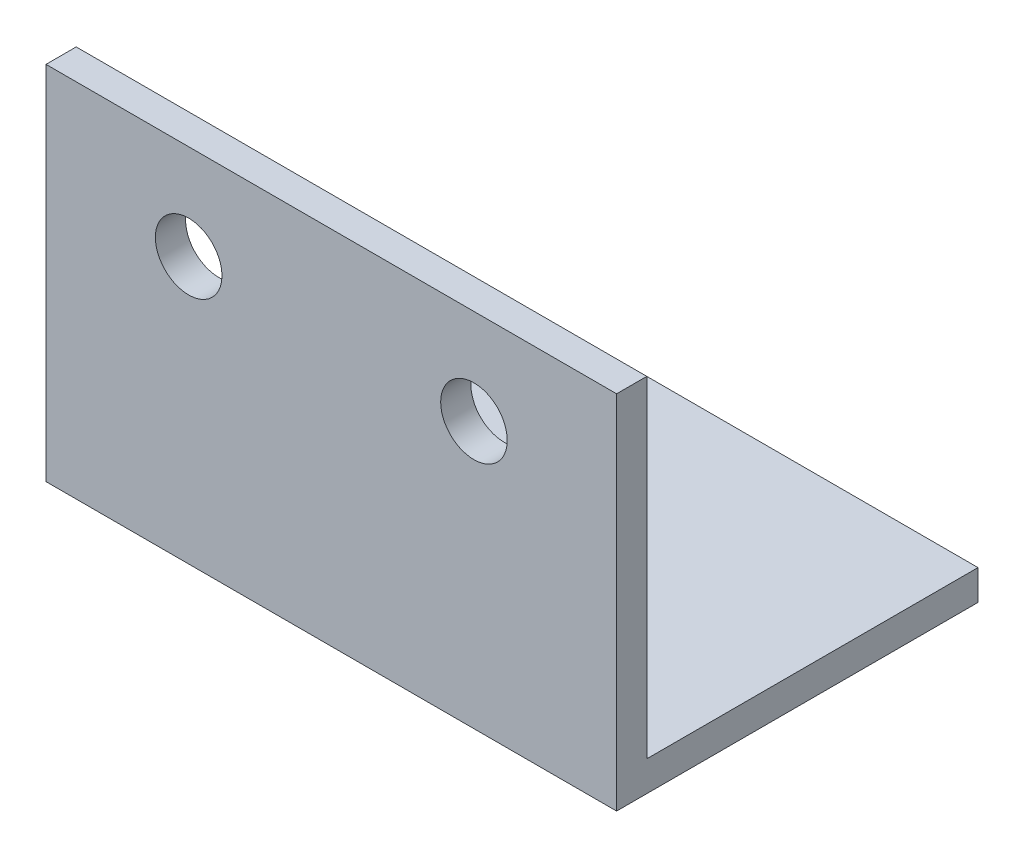
SolidWorks part; units mm, degrees
ref_plane "Front Plane" through (0, 0, 0) normal (0, 0, 1) x (1, 0, 0)
ref_plane "Top Plane" through (0, 0, 0) normal (0, 1, 0) x (1, 0, 0)
ref_plane "Right Plane" through (0, 0, 0) normal (1, 0, 0) x (0, 0, -1)
sketch "Sketch1" plane through (0, 0, 0) normal (0, 0, 1) x (1, 0, 0)
  line L1 (0, 0) -> (30, 0)
  line L2 (0, 0) -> (0, 38)
  line L3 (0, 38) -> (30, 38)
  line L4 (30, 0) -> (30, 38)
  dimension "D1" = 30
  dimension "D2" = 38
extrude "Boss-Extrude1" add sketch "Sketch1" along normal blind 3.175
sketch "Sketch2" plane through (0, 0, 0) normal (0, 0, -1) x (-1, 0, 0)
  line L0 (0, 38) -> (0, 0) construction
  line L1 (-30, 0) -> (0, 0)
  line L2 (-30, 0) -> (-30, 3.175)
  line L3 (-30, 3.175) -> (0, 3.175)
  line L4 (0, 0) -> (0, 3.175)
  dimension "D1" = 3.175
extrude "Boss-Extrude2" add sketch "Sketch2" along normal blind 34.825
sketch "Sketch3" plane through (0, 0, 0) normal (0, 0, -1) x (-1, 0, 0)
  line L0 (-30, 38) -> (0, 38) construction
  line L1 (-30, 3.175) -> (-30, 38) construction
  circle A0 centre (-15, 28) radius 4
  dimension "D1" = 8
  dimension "D2" = 10
  dimension "D3" = 15
extrude "Cut-Extrude1" cut sketch "Sketch3" against normal through all
sketch "Sketch4" plane through (0, 3.175, 0) normal (0, 1, 0) x (1, 0, 0)
  line L0 (0, 34.825) -> (30, 34.825) construction
  line L1 (30, 34.825) -> (30, 0) construction
  circle A0 centre (15, 24.825) radius 4
  dimension "D1" = 8
  dimension "D2" = 10
  dimension "D3" = 15
extrude "Cut-Extrude2" cut sketch "Sketch4" against normal through all
sketch "Croquis4" plane through (0, 0, 0) normal (0, 0, -1) x (-1, 0, 0)
  circle A0 centre (-15, 28) radius 4
  circle A1 centre (-15, 28) radius 3.5
extrude "Saliente-Extruir2" add sketch "Croquis4" against normal blind 5
sketch "Croquis5" plane through (0, 0, 0) normal (-1, 0, 0) x (0, 0, 1)
  line L0 (3.175, 38) -> (3.175, 0) construction
  line L1 (3.175, 32.6359) -> (7.154, 32.6359)
  line L2 (3.175, 32.6359) -> (3.175, 22.5356)
  line L3 (3.175, 22.5356) -> (7.154, 22.5356)
  line L4 (7.154, 32.6359) -> (7.154, 22.5356)
extrude "Cortar-Extruir1" cut sketch "Croquis5" against normal blind 36
sketch "Croquis6" plane through (0, 0, 0) normal (-1, 0, 0) x (0, 0, 1)
  line L1 (-34.825, 3.175) -> (3.175, 3.175)
  line L2 (-34.825, 3.175) -> (-34.825, 0)
  line L3 (-34.825, 0) -> (3.175, 0)
  line L4 (3.175, 3.175) -> (3.175, 0)
extrude "Saliente-Extruir3" add sketch "Croquis6" along normal blind 30
sketch "Croquis7" plane through (0, 0, 0) normal (-1, 0, 0) x (0, 0, 1)
  line L1 (3.175, 38) -> (0, 38)
  line L2 (3.175, 38) -> (3.175, 3.175)
  line L3 (3.175, 3.175) -> (0, 3.175)
  line L4 (0, 38) -> (0, 3.175)
extrude "Saliente-Extruir4" add sketch "Croquis7" along normal blind 30
sketch "Croquis8" plane through (0, 0, 0) normal (0, 0, -1) x (-1, 0, 0)
  line L0 (-30, 38) -> (30, 38) construction
  line L1 (30, 38) -> (30, 3.175) construction
  circle A0 centre (15, 28) radius 3.5
  dimension "D1" = 10
  dimension "D2" = 15
extrude "Cortar-Extruir2" cut sketch "Croquis8" against normal blind 30
sketch "Croquis9" plane through (0, 3.175, 0) normal (0, 1, 0) x (1, 0, 0)
  line L0 (-30, 34.825) -> (30, 34.825) construction
  line L1 (1.9546, 34.825) -> (30, 34.825)
  line L2 (1.9546, 34.825) -> (1.9546, 15.1563)
  line L3 (1.9546, 15.1563) -> (30, 15.1563)
  line L4 (30, 34.825) -> (30, 15.1563)
  line L5 (30, 34.825) -> (30, 0) construction
extrude "Saliente-Extruir5" add sketch "Croquis9" against normal blind 9
sketch "Croquis10" plane through (-30, 0, 0) normal (-1, 0, 0) x (0, 0, 1)
  line L1 (-34.825, 0) -> (-8.1256, 0)
  line L2 (-34.825, 0) -> (-34.825, -12.9467)
  line L3 (-34.825, -12.9467) -> (-8.1256, -12.9467)
  line L4 (-8.1256, 0) -> (-8.1256, -12.9467)
extrude "Cortar-Extruir3" cut sketch "Croquis10" against normal blind 65
sketch "Croquis11" plane through (0, 3.175, 0) normal (0, 1, 0) x (1, 0, 0)
  line L0 (-30, 34.825) -> (30, 34.825) construction
  circle A0 centre (0, 24.825) radius 3.5
  dimension "D1" = 10
  dimension "D2" = 7
extrude "Cortar-Extruir4" cut sketch "Croquis11" against normal blind 65
